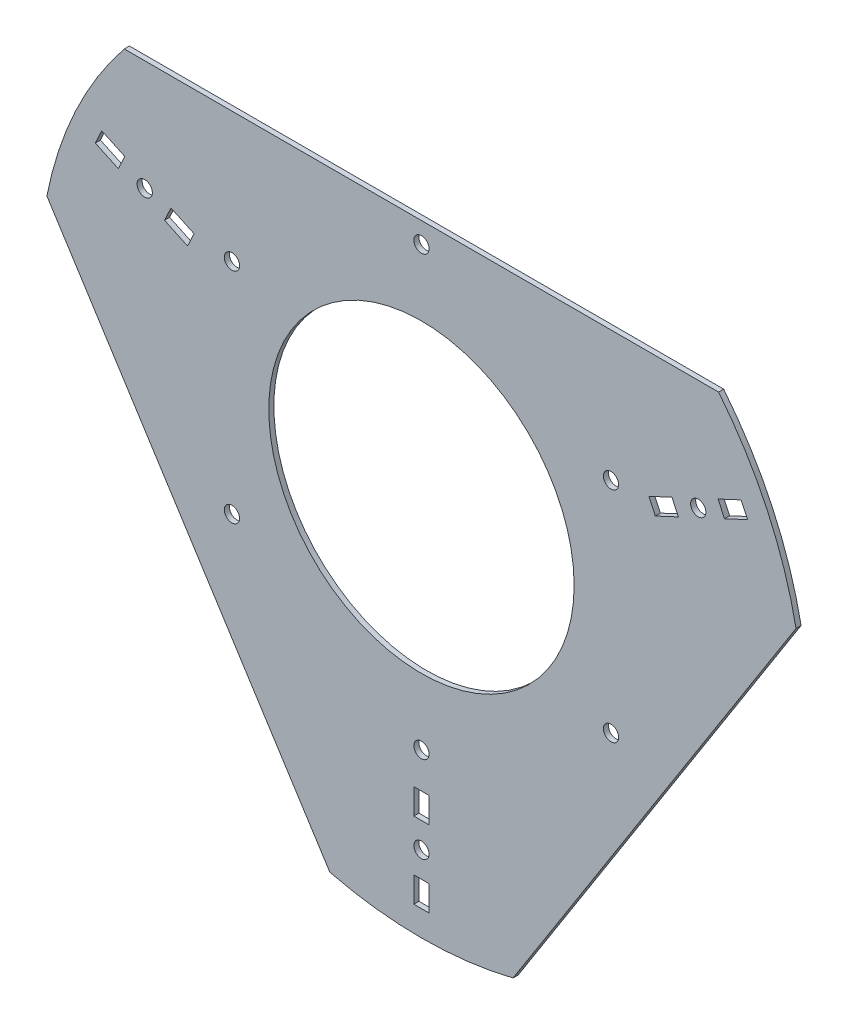
SolidWorks part; units mm, degrees
ref_plane "Front Plane" through (0, 0, 0) normal (0, 0, 1) x (1, 0, 0)
ref_plane "Top Plane" through (0, 0, 0) normal (0, 1, 0) x (1, 0, 0)
ref_plane "Right Plane" through (0, 0, 0) normal (1, 0, 0) x (0, 0, -1)
sketch "Sketch1" plane through (0, 0, 0) normal (0, 0, 1) x (1, 0, 0)
  line L0 (0, 0) -> (0, -75) construction
  line L1 (0, 0) -> (67.9731, 31.6964) construction
  line L2 (0, 0) -> (-67.9731, 31.6964) construction
  line L3 (-73.5936, 14.4564) -> (-18, -72.808)
  line L4 (18, -72.808) -> (73.5936, 14.4564)
  line L5 (58.3793, 47.0835) -> (-58.3793, 47.0835)
  circle A0 centre (0, 0) radius 30
  circle A1 centre (0, 0) radius 75 construction
  circle A2 centre (0, 0) radius 60 construction
  arc A3 (-73.5936, 14.4564) -> (-58.3793, 47.0835) centre (0, 0) cw
  arc A4 (58.3793, 47.0835) -> (73.5936, 14.4564) centre (0, 0) cw
  arc A5 (18, -72.808) -> (-18, -72.808) centre (0, 0) cw
  circle A6 centre (0, -43) radius 1.5
  circle A7 centre (-37.2391, -21.5) radius 1.5
  circle A8 centre (-37.2391, 21.5) radius 1.5
  circle A9 centre (0, 43) radius 1.5
  circle A10 centre (37.2391, 21.5) radius 1.5
  circle A11 centre (37.2391, -21.5) radius 1.5
  point P19 (27.3026, 35.9927)
  point P20 (0, 0)
  point P32 (0, 0)
  line B0 (0, -55) -> (0, -65) construction
  line B1 (1.5, -55) -> (1.5, -50)
  line B2 (1.5, -55) -> (-1.5, -55)
  line B3 (-1.5, -55) -> (-1.5, -50)
  line B4 (1.5, -50) -> (-1.5, -50)
  line B5 (1.5, -65) -> (1.5, -70)
  line B6 (1.5, -65) -> (-1.5, -65)
  line B7 (-1.5, -65) -> (-1.5, -70)
  line B8 (1.5, -70) -> (-1.5, -70)
  circle B9 centre (0, -60) radius 1.5
  line B10 (49.8469, 23.244) -> (58.91, 27.4702) construction
  line B11 (49.213, 24.6035) -> (44.6815, 22.4904)
  line B12 (49.213, 24.6035) -> (50.4809, 21.8845)
  line B13 (50.4809, 21.8845) -> (45.9493, 19.7715)
  line B14 (44.6815, 22.4904) -> (45.9493, 19.7715)
  line B15 (58.2761, 28.8296) -> (62.8076, 30.9427)
  line B16 (58.2761, 28.8296) -> (59.5439, 26.1107)
  line B17 (59.5439, 26.1107) -> (64.0755, 28.2238)
  line B18 (62.8076, 30.9427) -> (64.0755, 28.2238)
  circle B19 centre (54.3785, 25.3571) radius 1.5
  line B20 (-58.91, 27.4702) -> (-49.8469, 23.244) construction
  line B21 (-58.2761, 28.8296) -> (-62.8076, 30.9427)
  line B22 (-58.2761, 28.8296) -> (-59.5439, 26.1107)
  line B23 (-59.5439, 26.1107) -> (-64.0755, 28.2238)
  line B24 (-62.8076, 30.9427) -> (-64.0755, 28.2238)
  line B25 (-49.213, 24.6035) -> (-44.6815, 22.4904)
  line B26 (-49.213, 24.6035) -> (-50.4809, 21.8845)
  line B27 (-50.4809, 21.8845) -> (-45.9493, 19.7715)
  line B28 (-44.6815, 22.4904) -> (-45.9493, 19.7715)
  circle B29 centre (-54.3785, 25.3571) radius 1.5
  dimension "D1" = 60
  dimension "D2" = 150
  dimension "D4" = 120
  dimension "D8" = 3
  dimension "D3" = 115
  dimension "D5" = 18
  dimension "D6" = 18
  dimension "D7" = 43
  dimension "D9" = 6
sketch_block_instance "Trou M3 plots 3mm-1"
sketch_block "Trou M3 plots 3mm" parameters "D2"=3, "D1"=3, "D3"=5, "D4"=10
sketch_block_instance "Trou M3 plots 3mm-2"
sketch_block_instance "Trou M3 plots 3mm-3"
extrude "Boss-Extrude1" add sketch "Sketch1" along normal blind 1
